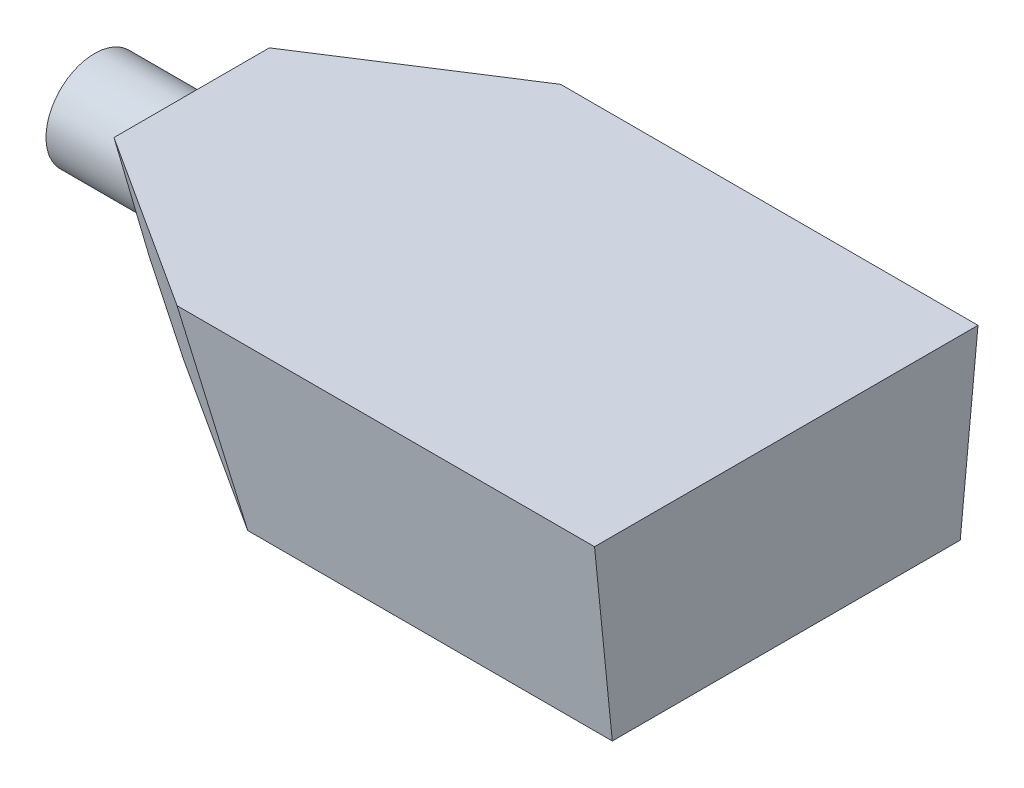
SolidWorks part; units mm, degrees
ref_plane "Front Plane" through (0, 0, 0) normal (0, 0, 1) x (1, 0, 0)
ref_plane "Top Plane" through (0, 0, 0) normal (0, 1, 0) x (1, 0, 0)
ref_plane "Right Plane" through (0, 0, 0) normal (1, 0, 0) x (0, 0, -1)
sketch "Sketch1" plane through (0, 0, 0) normal (0, 1, 0) x (1, 0, 0)
  line L0 (-43, 0) -> (-79.5, 0) construction
  line L1 (-43, -39.5) -> (43, -39.5)
  line L2 (-43, -39.5) -> (-43, 39.5)
  line L3 (-43, 39.5) -> (43, 39.5)
  line L4 (43, -39.5) -> (43, 39.5)
  line L5 (-43, -39.5) -> (43, 39.5) construction
  line L6 (-43, 39.5) -> (43, -39.5) construction
  line L7 (-79.5, 16) -> (-79.5, -16)
  line L8 (-79.5, 16) -> (-43, 39.5)
  line L9 (-79.5, -16) -> (-43, -39.5)
  point P0 (0, 0)
  point P11 (-79.5, 0)
  dimension "D1" = 86
  dimension "D2" = 79
  dimension "D3" = 36.5
  dimension "D4" = 32
extrude "Boss-Extrude1" add sketch "Sketch1" along normal blind 36.5 contours L7 L9 L2 L8 | L1 L4 L3 L2
sketch "Sketch3" plane through (0, 0, 39.5) normal (0, 0, 1) x (1, 0, 0)
  line L0 (43, 0) -> (-32.1, 0) construction
  line L2 (43, 36.5) -> (-43, 36.5) construction
  line L3 (-79.5, 36.5) -> (-43, 36.5) construction
  line L4 (-43, 36.5) -> (-32.1, 0)
  dimension "D1" = 75.1
  dimension "D2" = 86
sketch "Sketch7" plane through (0, 0, 0) normal (0, -1, 0) x (-1, 0, 0)
  line L0 (-43, 36.1597) -> (-43, -35.8403)
  line L1 (-43, -39.5) -> (-43, 39.5) construction
  line L2 (32.1, -35.8403) -> (-43, -35.8403)
  line L3 (32.1, -39.5) -> (32.1, -35.8403)
  point P5 (-43, 0.1597)
  dimension "D1" = 72
sketch "Sketch8" plane through (0, 0, 0) normal (0, -1, 0) x (-1, 0, 0)
  line L0 (79.5, -16) -> (32.1, -35.8403)
sketch "Sketch9" plane through (43, 0, 0) normal (1, 0, 0) x (0, 0, -1)
  line L0 (-39.5, 36.5) -> (-35.8403, 0)
  line L1 (-39.5, 0) -> (-35.8403, 0) construction
  line L2 (36.1597, 0) -> (-35.8403, 0) construction
  line L4 (-35.8403, 0) -> (-39.5, 0)
  line L5 (-39.5, 36.5) -> (-39.5, 0) construction
  line L6 (-39.5, 0) -> (-39.5, 36.5)
ref_plane "Plane1" through (0, -3.5578, 35.4836) normal (0, -0.0998, 0.995) x (1, 0, 0)
ref_plane "Plane2" through (-24.2527, -11.0195, 37.6691) normal (-0.5257, -0.2388, 0.8165) x (0.8507, -0.1476, 0.5045)
sketch "Sketch14" plane through (-24.2527, -11.0195, 37.6691) normal (-0.5257, -0.2388, 0.8165) x (0.8507, -0.1476, 0.5045)
  line L2 (-9.2246, 10.0628) -> (-22.0378, 46.1221)
  line L5 (-56.6103, -14.3453) -> (-9.2246, 10.0628)
  line L6 (-22.0378, 46.1221) -> (-64.9443, 39.5241)
  line L7 (-64.9443, 39.5241) -> (-109.4905, 32.6739)
  line L8 (-109.4905, 32.6739) -> (-56.6103, -14.3453)
extrude "Cut-Extrude4" cut sketch "Sketch14" along normal through all
sketch "Sketch15" plane through (0, -3.5578, 35.4836) normal (0, -0.0998, 0.995) x (1, 0, 0)
  line L2 (43, 3.5756) -> (43, 40.2586)
  line L3 (43, 40.2586) -> (-43, 40.2586)
  line L4 (-43, 40.2586) -> (-38.6217, -4.1368)
  line L5 (-38.6217, -4.1368) -> (43, 3.5756)
extrude "Cut-Extrude6" cut sketch "Sketch15" along normal through all
mirror "Mirror7" about plane through (0, 0, 0) normal (0, 0, 1) of "Cut-Extrude6", "Cut-Extrude4"
sketch "Sketch17" plane through (0, 0, 0) normal (0, -1, 0) x (-1, 0, 0)
  line L0 (-43, 0) -> (68.7, 0) construction
  line L1 (-43, -35.8403) -> (-43, 35.8403) construction
  line L2 (68.7, -7.599) -> (68.7, 7.599)
  point P8 (68.7, 0)
  point P9 (68.7, 0)
  dimension "D1" = 111.7
sketch "Sketch20" plane through (-79.5, 0, 0) normal (-1, 0, 0) x (0, 0, 1)
  line L0 (0, 36.5) -> (0, 6.5)
  line L1 (-16, 36.5) -> (16, 36.5) construction
  line L2 (-5, 6.5) -> (5, 6.5)
  point P8 (0, 6.5)
  dimension "D1" = 30
  dimension "D2" = 10
ref_plane "Plane3" through (-18.2678, -30.3527, 0) normal (-0.5157, -0.8568, 0) x (-0.8568, 0.5157, 0)
sketch "Sketch23" plane through (-18.2678, -30.3527, 0) normal (-0.5157, -0.8568, 0) x (-0.8568, 0.5157, 0)
  line L1 (28.3883, 49.9715) -> (80.8847, 49.9715)
  line L2 (28.3883, 49.9715) -> (28.3883, -45.2085)
  line L3 (28.3883, -45.2085) -> (80.8847, -45.2085)
  line L4 (80.8847, 49.9715) -> (80.8847, -45.2085)
extrude "Cut-Extrude9" cut sketch "Sketch23" along normal through all
sketch "Sketch25" plane through (-79.5, 0, 0) normal (-1, 0, 0) x (0, 0, 1)
  line L0 (16, 36.5) -> (8.6866, 11.5)
  line L1 (7.224, 6.5) -> (16, 36.5) construction
  dimension "D1" = 25
ref_plane "Plane5" through (-35.6345, -23.5126, 31.8888) normal (-0.6687, -0.4412, 0.5984) x (0.4995, 0.3296, 0.8012)
sketch "Sketch26" plane through (-35.6345, -23.5126, 31.8888) normal (-0.6687, -0.4412, 0.5984) x (0.4995, 0.3296, 0.8012)
  line L1 (-47.2209, 78.2608) -> (32.818, 78.2608)
  line L2 (-47.2209, 78.2608) -> (-47.2209, 35.0249)
  line L3 (-47.2209, 35.0249) -> (32.818, 35.0249)
  line L4 (32.818, 78.2608) -> (32.818, 35.0249)
extrude "Cut-Extrude10" cut sketch "Sketch26" along normal through all
mirror "Mirror9" about plane through (0, 0, 0) normal (0, 0, 1) of "Cut-Extrude10"
sketch "Sketch27" plane through (-79.5, 0, 0) normal (-1, 0, 0) x (0, 0, 1)
  line L0 (0, 36.5) -> (0, 23.5)
  line L1 (-16, 36.5) -> (16, 36.5) construction
  circle A0 centre (0, 23.5) radius 10
  dimension "D1" = 13
extrude "Boss-Extrude2" add sketch "Sketch27" along normal blind 20
sketch "Sketch28" plane through (-99.5, 0, 0) normal (-1, 0, 0) x (0, 0, 1)
  circle A0 centre (0, 23.5) radius 9.1
extrude "Cut-Extrude11" cut sketch "Sketch28" against normal blind 20
